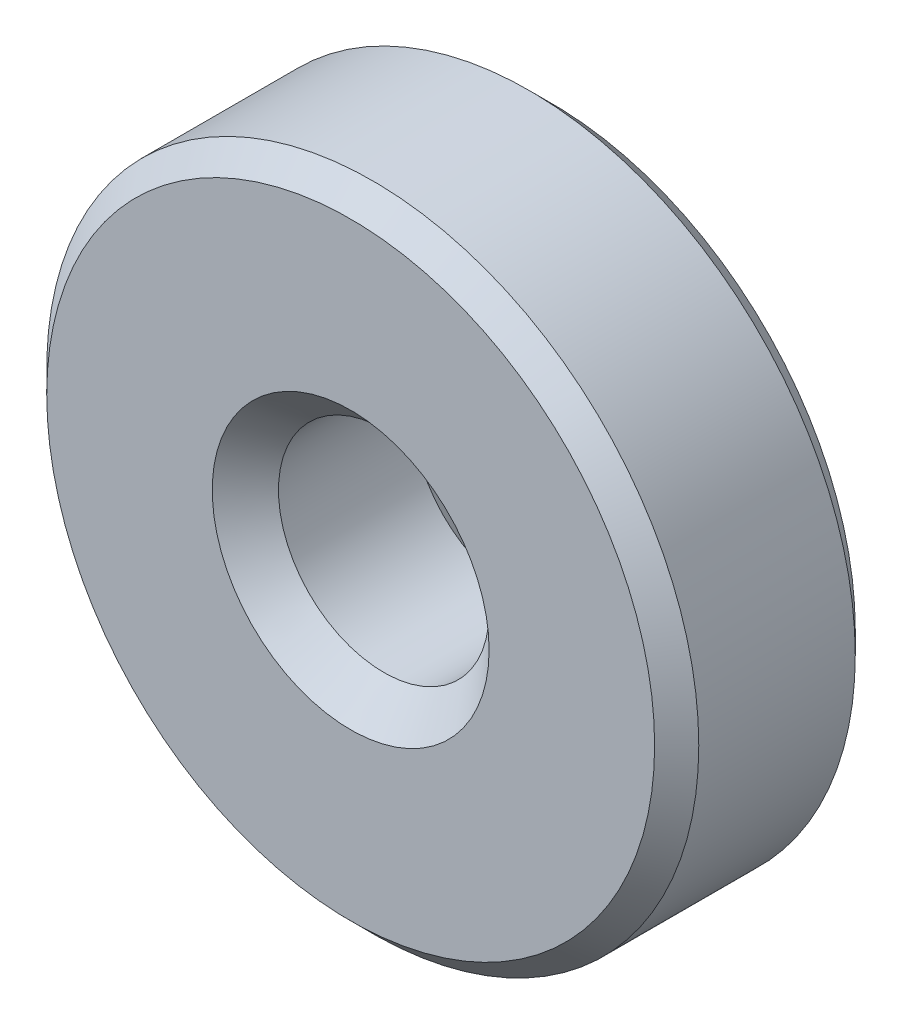
SolidWorks part; units mm, degrees
ref_plane "Front Plane" through (0, 0, 0) normal (0, 0, 1) x (1, 0, 0)
ref_plane "Top Plane" through (0, 0, 0) normal (0, 1, 0) x (1, 0, 0)
ref_plane "Right Plane" through (0, 0, 0) normal (1, 0, 0) x (0, 0, -1)
sketch "Sketch1" plane through (0, 0, 0) normal (0, 0, 1) x (1, 0, 0)
  circle A0 centre (0, 0) radius 6.5 construction
  circle A1 centre (0, 0) radius 2.1 construction
  point P4 (0, 6.5)
  dimension "ID" = 4.2
  dimension "OD" = 13
sketch "Sketch2" plane through (0, 0, 0) normal (1, 0, 0) x (0, 0, -1)
  line L0 (-2, 6.5) -> (2, 6.5) construction
  dimension "Length" = 4
sketch "Sketch3" plane through (0, 0, 0) normal (0, 0, 1) x (1, 0, 0)
  circle A0 centre (0, 0) radius 2.1 construction
  circle A1 centre (0, 0) radius 6.5 construction
  circle A2 centre (0, 0) radius 2.1
  circle A3 centre (0, 0) radius 6.5
extrude "Boss-Extrude1" add sketch "Sketch3" against normal up to vertex (2 mm away) and the other way up to vertex (2 mm away) up to point (0, 6.5, -2) other way up to point (0, 6.5, 2)
chamfer "Chamfer1" distance 0.44 angle 45 2 edges at (6.5, 0, 2) (6.5, 0, -2)
chamfer "Chamfer2" distance 0.66 angle 45 2 edges at (2.1, 0, 2) (2.1, 0, -2)
equation "\"D1@Chamfer1\"=(\"OD@Sketch1\"-\"ID@Sketch1\")*0.05"
equation "\"D1@Chamfer2\"=(\"OD@Sketch1\"-\"ID@Sketch1\")*0.075"
